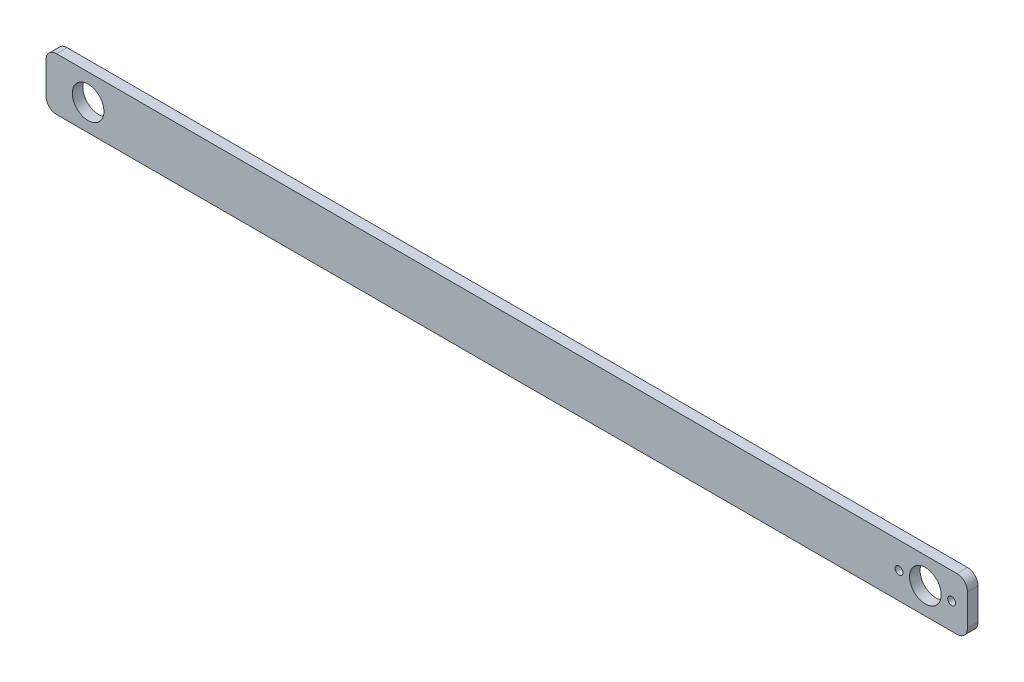
SolidWorks part; units mm, degrees
ref_plane "前视基准面" through (0, 0, 0) normal (0, 0, 1) x (1, 0, 0)
ref_plane "上视基准面" through (0, 0, 0) normal (0, 1, 0) x (1, 0, 0)
ref_plane "右视基准面" through (0, 0, 0) normal (1, 0, 0) x (0, 0, -1)
sketch "草图1" plane through (0, 0, 0) normal (0, 0, 1) x (1, 0, 0)
  line L1 (-170, 0) -> (5, 0)
  line L2 (-170, 0) -> (-170, -10)
  line L3 (-170, -10) -> (5, -10)
  line L4 (5, 0) -> (5, -10)
  point P4 (-170, -5)
  dimension "D1" = 175
  dimension "D2" = 10
extrude "凸台-拉伸1" add sketch "草图1" along normal blind 2
sketch "草图2" plane through (0, 0, 2) normal (0, 0, 1) x (1, 0, 0)
  line L0 (-170, -5) -> (-162, -5)
  line L1 (-170, 0) -> (-170, -10) construction
  circle A0 centre (-162, -5) radius 3
  dimension "D2" = 6
  dimension "D1" = 8
extrude "切除-拉伸1" cut sketch "草图2" against normal blind 15 and the other way blind 12
ref_plane "基准面1" through (-82.5, 0, 0) normal (-1, 0, 0) x (0, 0, 1)
sketch "草图3" plane through (0, 0, 2) normal (0, 0, 1) x (1, 0, 0)
  line L0 (5, -10) -> (5, 0) construction
  circle A0 centre (-3, -5) radius 3
  circle A1 centre (-8, -5) radius 0.75
  circle A2 centre (2, -5) radius 0.75
  dimension "D1" = 5
  dimension "D4" = 6
  dimension "D5" = 1.5
  dimension "D6" = 1.5
  dimension "D2" = 5
  dimension "D3" = 3
extrude "切除-拉伸2" cut sketch "草图3" against normal blind 10
fillet "圆角1" radius 2 4 edges at (5, 0, 1) (5, -10, 1) (-170, -10, 1) (-170, 0, 1)
